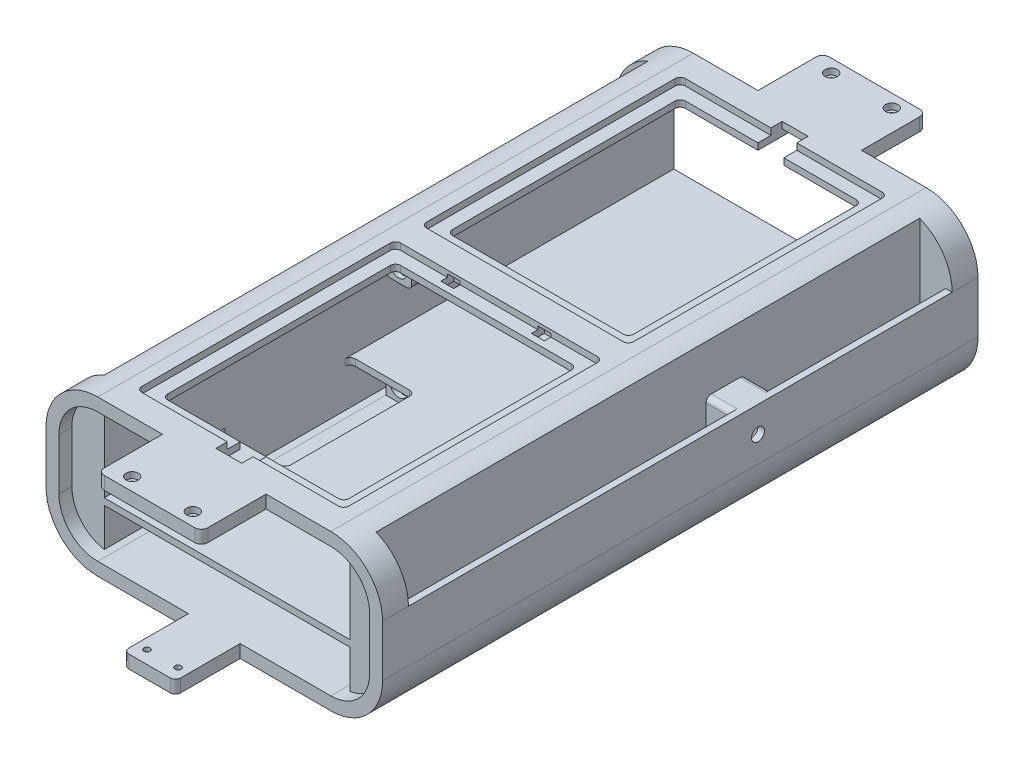
SolidWorks part; units mm, degrees
ref_plane "Front Plane" through (0, 0, 0) normal (0, 0, 1) x (1, 0, 0)
ref_plane "Top Plane" through (0, 0, 0) normal (0, 1, 0) x (1, 0, 0)
ref_plane "Right Plane" through (0, 0, 0) normal (1, 0, 0) x (0, 0, -1)
sketch "Layout" plane through (0, 0, 0) normal (0, 1, 0) x (1, 0, 0)
  line L3 (66.675, 139.7) -> (66.675, -139.7)
  line L4 (66.675, -139.7) -> (82.55, -139.7)
  line L8 (-82.55, -139.7) -> (-66.675, -139.7)
  line L9 (-66.675, -139.7) -> (-66.675, 139.7)
  line L10 (-66.675, 139.7) -> (-82.55, 139.7)
  line L12 (-82.55, 139.7) -> (-82.55, -139.7)
  line L13 (82.55, 139.7) -> (82.55, -139.7)
  line L14 (-66.675, 139.7) -> (66.675, 139.7)
  line L23 (66.675, 139.7) -> (82.55, 139.7)
  line L24 (-66.675, -139.7) -> (66.675, -139.7)
  line L26 (-60.325, -82.55) -> (-28.575, -82.55)
  line L27 (-60.325, -82.55) -> (-60.325, -19.05)
  line L28 (-60.325, -19.05) -> (-28.575, -19.05)
  line L29 (-28.575, -82.55) -> (-28.575, -19.05)
  point P0 (0, 139.7)
  point P13 (66.675, 0)
  dimension "D1" = 279.4
  dimension "D2" = 165.1
  dimension "D3" = 15.875
  dimension "D4" = 57.15
  dimension "D5" = 120.65
  dimension "D6" = 6.35
  dimension "D7" = 38.1
sketch "Battery" plane through (0, 0, 0) normal (0, 1, 0) x (1, 0, 0)
  line L1 (-23.495, 93.6625) -> (23.495, 93.6625)
  line L2 (-23.495, 93.6625) -> (-23.495, -45.2755)
  line L3 (-23.495, -45.2755) -> (23.495, -45.2755)
  line L4 (23.495, 93.6625) -> (23.495, -45.2755)
  point P4 (0, -45.2755)
  dimension "D1" = 138.938
  dimension "D2" = 46.99
sketch "Sketch1" plane through (0, 0, 0) normal (0, 0, 1) x (1, 0, 0)
  line L0 (-82.55, 0) -> (-82.55, 25.4)
  line L3 (82.55, 0) -> (82.55, 25.4)
  line L4 (-57.15, -25.4) -> (57.15, -25.4)
  line L5 (-57.15, 50.8) -> (57.15, 50.8)
  arc A0 (-82.55, 25.4) -> (-57.15, 50.8) centre (-57.15, 25.4) cw
  arc A1 (57.15, 50.8) -> (82.55, 25.4) centre (57.15, 25.4) cw
  arc A2 (82.55, 0) -> (57.15, -25.4) centre (57.15, 0) cw
  arc A3 (-57.15, -25.4) -> (-82.55, 0) centre (-57.15, 0) cw
  point P3 (0, -25.4)
  point P4 (0, 50.8)
  dimension "D1" = 76.2
  dimension "D2" = 165.1
  dimension "D3" = 25.4
extrude "Boss-Extrude1" add sketch "Sketch1" against normal mid plane 292.1
shell "Shell1" thickness 6.35
extrude "Boss-Extrude2" add sketch "Layout" along normal blind 3.175
sketch "Sketch3" plane through (0, 50.8, 0) normal (0, 1, 0) x (1, 0, 0)
  line L0 (-82.55, -139.7) -> (-66.675, -139.7) construction
  line L1 (-82.55, 133.35) -> (-66.675, 133.35)
  line L2 (-82.55, 133.35) -> (-82.55, -133.35)
  line L3 (-82.55, -133.35) -> (-66.675, -133.35)
  line L4 (-66.675, 133.35) -> (-66.675, -133.35)
  line L9 (-66.675, 139.7) -> (-82.55, 139.7) construction
  line L10 (-66.675, -139.7) -> (-66.675, 139.7) construction
  line L11 (0, -111.1454) -> (0, 111.1454) construction
  line L12 (82.55, -133.35) -> (66.675, -133.35)
  line L13 (82.55, 133.35) -> (66.675, 133.35)
  line L14 (66.675, 133.35) -> (66.675, -133.35)
  line L15 (82.55, 133.35) -> (82.55, -133.35)
  dimension "D1" = 15.875
  dimension "D2" = 6.35
  dimension "D3" = 6.35
extrude "Cut-Extrude1" cut sketch "Sketch3" against normal through all and the other way through all
sketch "Sketch4" plane through (0, 0, 0) normal (0, 1, 0) x (1, 0, 0)
  line L37 (66.675, 133.35) -> (82.55, 133.35)
  line L40 (82.55, 139.7) -> (60.325, 139.7)
  line L41 (60.325, 139.7) -> (60.325, -139.7)
  line L42 (66.675, 133.35) -> (66.675, -133.35)
  line L43 (66.675, -133.35) -> (76.2, -133.35)
  line L44 (76.2, -133.35) -> (76.2, -139.7)
  line L45 (76.2, -139.7) -> (60.325, -139.7)
  line L46 (0, -111.1454) -> (0, 111.1454) construction
  line L47 (-76.2, -139.7) -> (-60.325, -139.7)
  line L48 (-76.2, -133.35) -> (-76.2, -139.7)
  line L49 (-66.675, -133.35) -> (-76.2, -133.35)
  line L50 (-60.325, 139.7) -> (-60.325, -139.7)
  line L51 (-66.675, 133.35) -> (-66.675, -133.35)
  line L52 (-66.675, 133.35) -> (-82.55, 133.35)
  line L53 (-82.55, 133.35) -> (-82.55, 139.7)
  line L54 (-82.55, 139.7) -> (-60.325, 139.7)
  line L55 (82.55, 139.7) -> (82.55, 133.35)
  dimension "D1" = 6.35
  dimension "D2" = 6.35
  dimension "D3" = 6.35
extrude "Boss-Extrude3" add sketch "Sketch4" along normal up to next and the other way up to next contours L45 L44 L43 L42 L37 L55 L40 L41 | L54 L53 L52 L51 L49 L48 L47 L50
sketch "Sketch6" plane through (0, 0, -139.7) normal (0, 0, -1) x (-1, 0, 0)
  line L29 (-82.55, 0) -> (-60.325, 0)
  line L30 (-60.325, 0) -> (-60.325, -25.2008)
  line L32 (0, 111.1454) -> (0, -111.1454) construction
  line L33 (60.325, 0) -> (60.325, -25.2008)
  line L34 (82.55, 0) -> (60.325, 0)
  arc A10 (-82.55, 0) -> (-57.15, -25.4) centre (-57.15, 0) ccw construction
  arc A11 (-60.325, -25.2008) -> (-82.55, 0) centre (-57.15, 0) cw
  arc A12 (60.325, -25.2008) -> (82.55, 0) centre (57.15, 0) ccw
extrude "Boss-Extrude4" add sketch "Sketch6" against normal up to surface (279.4 mm away) up to face at (0, 8.9958, 139.7)
sketch "Sketch7" plane through (0, 0, -139.7) normal (0, 0, -1) x (-1, 0, 0)
  line L6 (0, 111.1454) -> (0, -111.1454) construction
  line L7 (79.375, 0) -> (82.55, 0)
  line L8 (79.375, 0) -> (79.375, 25.4)
  line L9 (79.375, 25.4) -> (82.55, 25.4)
  line L10 (82.55, 0) -> (82.55, 25.4)
  line L11 (-79.375, 0) -> (-82.55, 0)
  line L12 (-79.375, 0) -> (-79.375, 25.4)
  line L13 (-82.55, 0) -> (-82.55, 25.4)
  line L14 (-79.375, 25.4) -> (-82.55, 25.4)
  dimension "D1" = 3.175
extrude "Boss-Extrude5" add sketch "Sketch7" against normal up to surface (279.4 mm away) up to face at (0, 8.9958, 139.7)
sketch "Sketch8" plane through (0, 50.8, 0) normal (0, 1, 0) x (1, 0, 0)
  line L0 (-25.4, 146.05) -> (-25.4, 177.8)
  line L1 (57.15, 146.05) -> (-57.15, 146.05) construction
  line L2 (25.4, 146.05) -> (25.4, 177.8)
  line L3 (-25.4, 177.8) -> (25.4, 177.8)
  line L4 (-25.4, 146.05) -> (25.4, 146.05)
  line L5 (-82.55, 146.05) -> (-82.55, 133.35) construction
  line L6 (82.55, 146.05) -> (82.55, 133.35) construction
  dimension "D1" = 57.15
  dimension "D2" = 57.15
  dimension "D3" = 31.75
extrude "Boss-Extrude6" add sketch "Sketch8" against normal blind 6.35
fillet "Fillet1" radius 3.175 2 edges at (-25.4, 47.625, -177.8) (25.4, 47.625, -177.8)
hole_wizard "CBORE for #00 Binding Head Machine Screw1" positions "Sketch11" profile "Sketch12" counterbore size "#00" standard "ANSI Inch" end condition up to next
sketch "Sketch11" plane through (0, 50.8, 0) normal (0, -1, 0) x (-1, 0, 0)
  line L1 (-25.4, 146.05) -> (-25.4, 174.625) construction
  line L2 (-22.225, 177.8) -> (22.225, 177.8) construction
  line L3 (25.4, 174.625) -> (25.4, 146.05) construction
  point P0 (14.85, 171.45)
  point P2 (-14.85, 171.45)
  dimension "D1" = 10.55
  dimension "D2" = 6.35
  dimension "D3" = 10.55
  dimension "D4" = 6.35
sketch "Sketch12" plane through (-14.85, 50.8, -171.45) normal (1, 0, 0) x (0, 0, 1)
  line L0 (0, 0) -> (0, 6.35)
  line L1 (0, 6.35) -> (1.5, 6.35)
  line L3 (1.5, 6.35) -> (1.5, 3)
  line L4 (1.5, 3) -> (3, 3)
  line L5 (3, 3) -> (3, 0)
  line L7 (3, 0) -> (0, 0)
  line L11 (0, -6.35) -> (0, 107.95) construction
  dimension "Thru Hole Dia." = 3
  dimension "Thru Hole Depth" = 6.35
  dimension "C'Bore Dia." = 6
  dimension "C'Bore Depth" = 3
sketch "Sketch13" plane through (0, -25.4, 0) normal (0, -1, 0) x (1, 0, 0)
  line L0 (-12.7, -146.05) -> (-12.7, -177.8)
  line L1 (-57.15, -146.05) -> (57.15, -146.05) construction
  line L2 (-12.7, -177.8) -> (12.7, -177.8)
  line L3 (12.7, -177.8) -> (12.7, -146.05)
  line L4 (12.7, -146.05) -> (-12.7, -146.05)
  line L7 (-82.55, -146.05) -> (-82.55, 146.05) construction
  line L8 (82.55, -146.05) -> (82.55, 146.05) construction
  dimension "D1" = 31.75
  dimension "D2" = 69.85
  dimension "D3" = 69.85
extrude "Boss-Extrude7" add sketch "Sketch13" against normal blind 6.35
fillet "Fillet2" radius 2.54 2 edges at (12.7, -22.225, -177.8) (-12.7, -22.225, -177.8)
hole_wizard "CBORE for #00 Binding Head Machine Screw2" positions "Sketch14" profile "Sketch15" counterbore size "#00" standard "ANSI Inch"
sketch "Sketch14" plane through (0, -25.4, 0) normal (0, -1, 0) x (-1, 0, 0)
  line L0 (12.7, 146.05) -> (12.7, 175.26) construction
  line L1 (-12.7, 175.26) -> (-12.7, 146.05) construction
  line L2 (10.16, 177.8) -> (-10.16, 177.8) construction
  point P0 (-7.62, 171.45)
  point P2 (7.62, 171.45)
  dimension "D1" = 5.08
  dimension "D2" = 5.08
  dimension "D3" = 6.35
  dimension "D4" = 6.35
sketch "Sketch15" plane through (7.62, -25.4, -171.45) normal (1, 0, 0) x (0, 0, -1)
  line L0 (0, 0) -> (0, 6.35)
  line L1 (0, 6.35) -> (1.5, 6.35)
  line L3 (1.5, 6.35) -> (1.5, 3)
  line L4 (1.5, 3) -> (3, 3)
  line L5 (3, 3) -> (3, 0)
  line L7 (3, 0) -> (0, 0)
  line L11 (0, -6.35) -> (0, 107.95) construction
  dimension "Thru Hole Dia." = 3
  dimension "Thru Hole Depth" = 6.35
  dimension "C'Bore Dia." = 6
  dimension "C'Bore Depth" = 3
mirror "Mirror3" about plane through (0, 0, 0) normal (0, 0, 1) of "CBORE for #00 Binding Head Machine Screw2", "Fillet2", "Boss-Extrude7"
mirror "Mirror6" about plane through (0, 0, 0) normal (0, 0, 1) of "Boss-Extrude6", "Fillet1", "CBORE for #00 Binding Head Machine Screw1"
sketch "Sketch16" plane through (0, 50.8, 0) normal (0, 1, 0) x (1, 0, 0)
  line L0 (-50.8, 133.35) -> (50.8, 133.35)
  line L1 (50.8, 133.35) -> (50.8, -133.35)
  line L2 (50.8, -133.35) -> (-50.8, -133.35)
  line L3 (-50.8, -133.35) -> (-50.8, 133.35)
  line L4 (-25.4, 146.05) -> (-57.15, 146.05) construction
  line L6 (57.15, 146.05) -> (57.15, -146.05) construction
  line L7 (-57.15, 146.05) -> (-57.15, -146.05) construction
  line L8 (57.15, -146.05) -> (25.4, -146.05) construction
  line L9 (-57.15, -6.35) -> (57.15, -6.35)
  line L10 (-57.15, -6.35) -> (-57.15, 6.35)
  line L11 (-57.15, 6.35) -> (57.15, 6.35)
  line L12 (57.15, -6.35) -> (57.15, 6.35)
  line L13 (-57.15, -6.35) -> (57.15, 6.35) construction
  line L14 (-57.15, 6.35) -> (57.15, -6.35) construction
  point P6 (-41.275, 146.05)
  point P7 (0, 0)
  dimension "D1" = 12.7
  dimension "D2" = 12.7
  dimension "D3" = 6.35
  dimension "D4" = 6.35
  dimension "D5" = 12.7
extrude "Cut-Extrude2" cut sketch "Sketch16" against normal blind 3.175 contours L3 L11 L1 L0 | L9 L3 L2 L1
sketch "Sketch17" plane through (0, 50.8, 0) normal (0, 1, 0) x (1, 0, 0)
  line L0 (50.8, 133.35) -> (50.8, 6.35) construction
  line L1 (-44.45, 127) -> (44.45, 127)
  line L2 (-44.45, 127) -> (-44.45, -127)
  line L3 (-44.45, -127) -> (44.45, -127)
  line L4 (44.45, 127) -> (44.45, -127)
  line L5 (50.8, 133.35) -> (-50.8, 133.35) construction
  line L7 (-50.8, 133.35) -> (-50.8, 6.35) construction
  line L9 (50.8, -133.35) -> (-50.8, -133.35) construction
  line L12 (-44.45, -12.7) -> (44.45, -12.7)
  line L13 (-44.45, -12.7) -> (-44.45, 12.7)
  line L14 (-44.45, 12.7) -> (44.45, 12.7)
  line L15 (44.45, -12.7) -> (44.45, 12.7)
  line L16 (-44.45, -12.7) -> (44.45, 12.7) construction
  line L17 (-44.45, 12.7) -> (44.45, -12.7) construction
  point P4 (0, 0)
  dimension "D1" = 6.35
  dimension "D2" = 6.35
  dimension "D3" = 6.35
  dimension "D4" = 6.35
  dimension "D5" = 25.4
extrude "Cut-Extrude3" cut sketch "Sketch17" against normal up to next contours L2 L14 L4 L1 | L12 L2 L3 L4
sketch "Sketch29" plane through (0, 44.45, 0) normal (0, -1, 0) x (1, 0, 0)
  line L1 (-25.4, 9.525) -> (-19.05, 9.525)
  line L2 (-25.4, 9.525) -> (-25.4, 3.175)
  line L3 (-25.4, 3.175) -> (-19.05, 3.175)
  line L4 (-19.05, 9.525) -> (-19.05, 3.175)
  line L5 (0, -111.1454) -> (0, 111.1454) construction
  line L6 (25.4, 3.175) -> (19.05, 3.175)
  line L7 (25.4, 9.525) -> (25.4, 3.175)
  line L8 (25.4, 9.525) -> (19.05, 9.525)
  line L9 (19.05, 9.525) -> (19.05, 3.175)
  line L10 (111.1454, 0) -> (-111.1454, 0) construction
  line L11 (-25.4, -3.175) -> (-19.05, -3.175)
  line L12 (-25.4, -9.525) -> (-25.4, -3.175)
  line L13 (-25.4, -9.525) -> (-19.05, -9.525)
  line L14 (-19.05, -9.525) -> (-19.05, -3.175)
  line L15 (25.4, -3.175) -> (19.05, -3.175)
  line L16 (19.05, -9.525) -> (19.05, -3.175)
  line L17 (25.4, -9.525) -> (19.05, -9.525)
  line L18 (25.4, -9.525) -> (25.4, -3.175)
  line L20 (44.45, 12.7) -> (-44.45, 12.7) construction
  dimension "D1" = 19.05
  dimension "D2" = 6.35
  dimension "D3" = 6.35
  dimension "D4" = 3.175
extrude "Cut-Extrude11" cut sketch "Sketch29" against normal offset from surface (4.7625 mm away) 1.5875 up to face at (-14.85, 50.8, 174.45)
sketch "Sketch21" plane through (0, 44.45, 0) normal (0, 1, 0) x (1, 0, 0)
  line L1 (-6.35, 127) -> (6.35, 127)
  line L2 (-6.35, 127) -> (-6.35, 146.05)
  line L3 (-6.35, 146.05) -> (6.35, 146.05)
  line L4 (6.35, 127) -> (6.35, 146.05)
  line L9 (44.45, 127) -> (-44.45, 127) construction
  point P4 (0, 127)
  dimension "D1" = 19.05
  dimension "D2" = 12.7
extrude "Cut-Extrude7" cut sketch "Sketch21" along normal offset from surface (3.175 mm away) 3.175 up to face at (-14.85, 50.8, 174.45)
sketch "Sketch31" plane through (0, 50.8, 0) normal (0, 1, 0) x (1, 0, 0)
  line L1 (-6.35, 133.35) -> (6.35, 133.35)
  line L2 (-6.35, 133.35) -> (-6.35, 138.9062)
  line L3 (-6.35, 138.9062) -> (6.35, 138.9062)
  line L4 (6.35, 133.35) -> (6.35, 138.9062)
  dimension "D1" = 5.5562
extrude "Cut-Extrude12" cut sketch "Sketch31" against normal up to next
mirror "Mirror7" about plane through (0, 0, 0) normal (0, 0, 1) of "Cut-Extrude12", "Cut-Extrude7"
sketch "Sketch24" plane through (0, -19.05, 0) normal (0, 1, 0) x (1, 0, 0)
  line L0 (-41.91, 0) -> (41.91, 0) construction
  line L1 (-57.15, 0) -> (-44.45, 0)
  line L2 (-57.15, 0) -> (-57.15, 4.7625)
  line L3 (-57.15, 4.7625) -> (-44.45, 4.7625)
  line L4 (-44.45, 0) -> (-44.45, 4.7625)
  line L6 (-57.15, 146.05) -> (-57.15, -146.05) construction
  line L12 (44.45, 0) -> (57.15, 0)
  line L13 (44.45, 0) -> (44.45, 4.7625)
  line L14 (44.45, 4.7625) -> (57.15, 4.7625)
  line L15 (57.15, 0) -> (57.15, 4.7625)
  line L16 (57.15, 146.05) -> (57.15, -146.05) construction
  dimension "D1" = 4.7625
  dimension "D2" = 12.7
extrude "Boss-Extrude9" add sketch "Sketch24" along normal blind 12.7
sketch "Sketch26" plane through (0, 44.45, 0) normal (0, -1, 0) x (1, 0, 0)
  line L0 (0, -41.91) -> (0, 41.91) construction
  line L1 (57.15, -4.7625) -> (44.45, -4.7625)
  line L2 (-57.15, 0) -> (-44.45, 0)
  line L3 (-57.15, 0) -> (-57.15, -4.7625)
  line L4 (-57.15, -4.7625) -> (-44.45, -4.7625)
  line L6 (44.45, 0) -> (44.45, -4.7625)
  line L7 (57.15, 0) -> (44.45, 0)
  line L8 (57.15, 0) -> (57.15, -4.7625)
  line L10 (-44.45, 0) -> (-44.45, -4.7625)
  line L11 (41.91, 0) -> (-41.91, 0) construction
  line L12 (-44.45, -12.7) -> (-44.45, -127) construction
  dimension "D1" = 4.7625
  dimension "D2" = 12.7
extrude "Boss-Extrude10" add sketch "Sketch26" along normal blind 12.7
mirror "Mirror9" about plane through (0, 0, 0) normal (0, 0, 1) of "Boss-Extrude10", "Boss-Extrude9"
fillet "Fillet4" radius 2.54 28 edges at (-50.8, 49.2125, -133.35) (-44.45, 46.0375, -127) (44.45, 46.0375, -127) (50.8, 49.2125, -133.35) (50.8, 49.2125, -6.35) (44.45, 46.0375, -12.7) (-44.45, 46.0375, -12.7) (-50.8, 49.2125, -6.35) (-50.8, 49.2125, 6.35) (-44.45, 46.0375, 12.7) (44.45, 46.0375, 12.7) (50.8, 49.2125, 6.35) (44.45, 46.0375, 127) (50.8, 49.2125, 133.35) (-50.8, 49.2125, 133.35) (-44.45, 46.0375, 127) (57.15, 31.75, 0) (44.45, 31.75, 0) (-57.15, 31.75, 0) (-44.45, 31.75, 0) (57.15, -6.35, 0) (44.45, -6.35, 0) (-57.15, -6.35, 0) (-44.45, -6.35, 0) (-28.575, 1.5875, 82.55) (-60.325, 1.5875, 82.55) (-60.325, 1.5875, 19.05) (-28.575, 1.5875, 19.05)
hole_wizard "CBORE for M3 Hex Head Machine Screw1" positions "Sketch39" profile "Sketch40" counterbore size "M3" standard "ANSI Metric" end condition through all
sketch "Sketch39" plane through (0, 0, 4.7625) normal (0, 0, 1) x (1, 0, 0)
  line L0 (-44.45, 34.29) -> (-44.45, 44.45) construction
  line L3 (44.45, 34.29) -> (44.45, 44.45) construction
  line L4 (-54.61, 31.75) -> (-46.99, 31.75) construction
  line L5 (-46.99, -6.35) -> (-54.61, -6.35) construction
  point P0 (-50.8, 38.1)
  point P2 (50.8, 38.1)
  point P4 (50.8, -12.7)
  point P6 (-50.8, -12.7)
  dimension "D1" = 6.35
  dimension "D2" = 6.35
  dimension "D3" = 6.35
  dimension "D4" = 6.35
sketch "Sketch40" plane through (-50.8, 38.1, 4.7625) normal (1, 0, 0) x (0, -1, 0)
  line L0 (0, 0) -> (0, 182.5625)
  line L1 (0, 182.5625) -> (1.7, 182.5625)
  line L3 (1.7, 182.5625) -> (1.7, 2.3)
  line L4 (1.7, 2.3) -> (4.2, 2.3)
  line L5 (4.2, 2.3) -> (4.2, 0)
  line L7 (4.2, 0) -> (0, 0)
  line L11 (0, -6.35) -> (0, 107.95) construction
  dimension "Thru Hole Dia." = 3.4
  dimension "Thru Hole Depth" = 182.5625
  dimension "C'Bore Dia." = 8.4
  dimension "C'Bore Depth" = 2.3
sketch "Sketch34" plane through (60.325, 0, 0) normal (-1, 0, 0) x (0, 0, 1)
  line L0 (-139.7, 3.175) -> (139.7, 3.175) construction
  line L1 (-139.7, 3.175) -> (-139.7, 44.1836) construction
  circle A0 centre (-38.1, 12.7) radius 3.175
  dimension "D1" = 6.35
  dimension "D2" = 9.525
  dimension "D3" = 101.6
extrude "Cut-Extrude15" cut sketch "Sketch34" against normal through all
sketch "Sketch35" plane through (0, 0, 0) normal (0, 1, 0) x (1, 0, 0)
  line L0 (66.675, 44.45) -> (79.375, 44.45)
  line L1 (66.675, 133.35) -> (66.675, -133.35) construction
  line L2 (79.375, -133.35) -> (79.375, 133.35) construction
  line L3 (66.675, 47.625) -> (79.375, 47.625)
  line L4 (66.675, 31.75) -> (79.375, 31.75)
  line L5 (66.675, 28.575) -> (79.375, 28.575)
  line L6 (66.675, 41.275) -> (60.325, 41.275) construction
  line L7 (60.325, 34.925) -> (66.675, 34.925) construction
  line L8 (66.675, 47.625) -> (66.675, 44.45)
  line L9 (79.375, 47.625) -> (79.375, 44.45)
  line L10 (79.375, 31.75) -> (79.375, 28.575)
  line L11 (66.675, 31.75) -> (66.675, 28.575)
  dimension "D1" = 3.175
  dimension "D2" = 3.175
  dimension "D3" = 3.175
  dimension "D4" = 3.175
extrude "Boss-Extrude11" add sketch "Sketch35" along normal up to surface (25.4 mm away) up to face at (80.9625, 25.4, 0)
sketch "Sketch36" plane through (0, 0, -44.45) normal (0, 0, 1) x (1, 0, 0)
  line L0 (66.675, 25.4) -> (66.675, 0) construction
  line L1 (66.675, 25.4) -> (79.375, 25.4)
  line L2 (66.675, 25.4) -> (66.675, 22.225)
  line L3 (66.675, 22.225) -> (79.375, 22.225)
  line L4 (79.375, 25.4) -> (79.375, 22.225)
  line L5 (66.675, 25.4) -> (79.375, 25.4) construction
  line L6 (79.375, 25.4) -> (79.375, 0) construction
  dimension "D1" = 3.175
extrude "Boss-Extrude12" add sketch "Sketch36" along normal up to surface (12.7 mm away) up to face at (73.025, 12.7, -31.75)
fillet "Fillet5" radius 2.54 2 edges at (73.025, 25.4, -47.625) (73.025, 25.4, -28.575)
sketch "Sketch41" [suppressed] plane through (0, 0, 0) normal (0, 0, 1) x (1, 0, 0)
  line L1 (-123.8358, -84.2411) -> (123.8358, -84.2411)
  line L2 (-123.8358, -84.2411) -> (-123.8358, 84.2411)
  line L3 (-123.8358, 84.2411) -> (123.8358, 84.2411)
  line L4 (123.8358, -84.2411) -> (123.8358, 84.2411)
  line L5 (-123.8358, -84.2411) -> (123.8358, 84.2411) construction
  line L6 (-123.8358, 84.2411) -> (123.8358, -84.2411) construction
extrude "Cut-Extrude16" [suppressed] cut sketch "Sketch41" against normal through all
sketch "Sketch42" [suppressed] plane through (0, 0, 0) normal (0, 0, 1) x (1, 0, 0)
  line L1 (-129.6401, -101.0412) -> (129.6401, -101.0412)
  line L2 (-129.6401, -101.0412) -> (-129.6401, 101.0412)
  line L3 (-129.6401, 101.0412) -> (129.6401, 101.0412)
  line L4 (129.6401, -101.0412) -> (129.6401, 101.0412)
  line L5 (-129.6401, -101.0412) -> (129.6401, 101.0412) construction
  line L6 (-129.6401, 101.0412) -> (129.6401, -101.0412) construction
extrude "Cut-Extrude17" [suppressed] cut sketch "Sketch42" along normal through all
